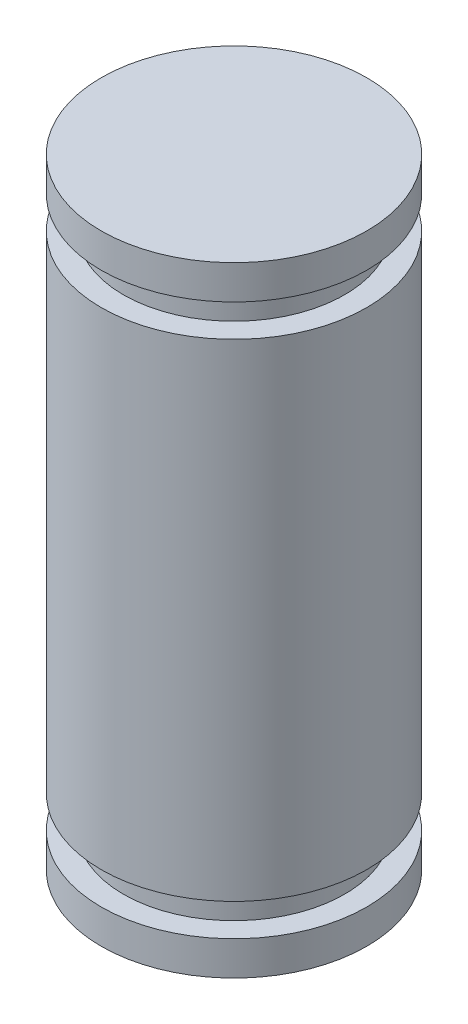
SolidWorks part; units mm, degrees
ref_plane "Front Plane" through (0, 0, 0) normal (0, 0, 1) x (1, 0, 0)
ref_plane "Top Plane" through (0, 0, 0) normal (0, 1, 0) x (1, 0, 0)
ref_plane "Right Plane" through (0, 0, 0) normal (1, 0, 0) x (0, 0, -1)
sketch "Sketch1" plane through (0, 0, 0) normal (0, 0, 1) x (1, 0, 0)
  line L16 (0, 1.5) -> (0, 12.5)
  line L17 (0, 12.5) -> (-0.5, 12.5)
  line L18 (-0.5, 12.5) -> (-0.5, 13.23)
  line L19 (-0.5, 13.23) -> (0, 13.23)
  line L20 (0, 13.23) -> (0, 14)
  line L21 (0, 14) -> (-3, 14)
  line L22 (-3, 14) -> (-3, 0)
  line L23 (-3, 0) -> (0, 0)
  line L24 (0, 7) -> (-1.3515, 7) construction
  line L25 (0, 1.5) -> (-0.5, 1.5)
  line L26 (-0.5, 1.5) -> (-0.5, 0.77)
  line L27 (-0.5, 0.77) -> (0, 0.77)
  line L28 (0, 0.77) -> (0, 0)
  dimension "D1" = 14
  dimension "D2" = 0.73
  dimension "D3" = 11
  dimension "D4" = 0.5
  dimension "D5" = 3
revolve "Revolve1" add sketch "Sketch1" angle 360 about L22
